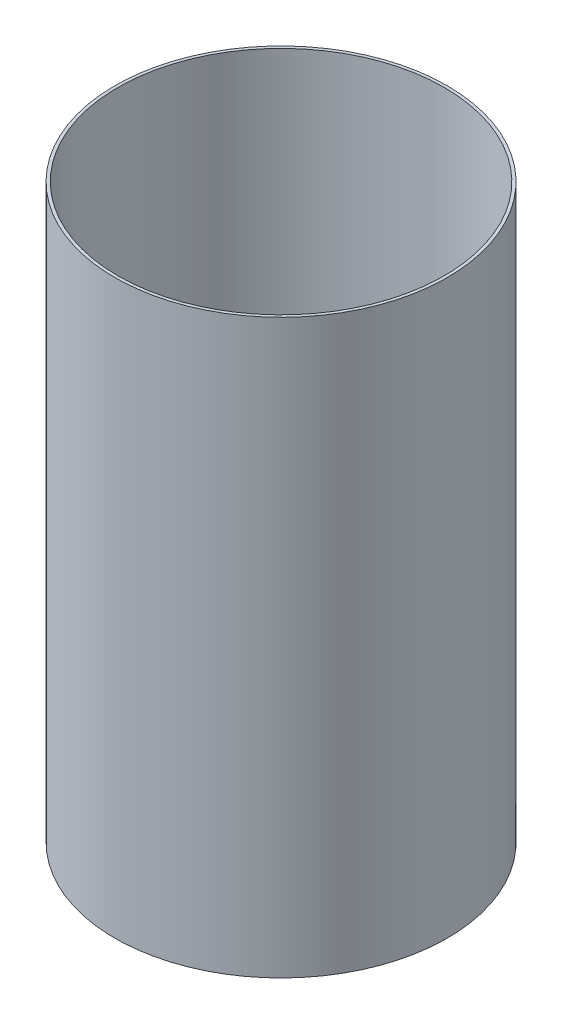
SolidWorks part; units mm, degrees
ref_plane "Front Plane" through (0, 0, 0) normal (0, 0, 1) x (1, 0, 0)
ref_plane "Top Plane" through (0, 0, 0) normal (0, 1, 0) x (1, 0, 0)
ref_plane "Right Plane" through (0, 0, 0) normal (1, 0, 0) x (0, 0, -1)
sketch "Sketch1" plane through (0, 0, 0) normal (0, 1, 0) x (1, 0, 0)
  circle A0 centre (0, 0) radius 88.519
  circle A1 centre (0, 0) radius 86.9315
extrude "Boss-Extrude1" add sketch "Sketch1" along normal blind 304.8
